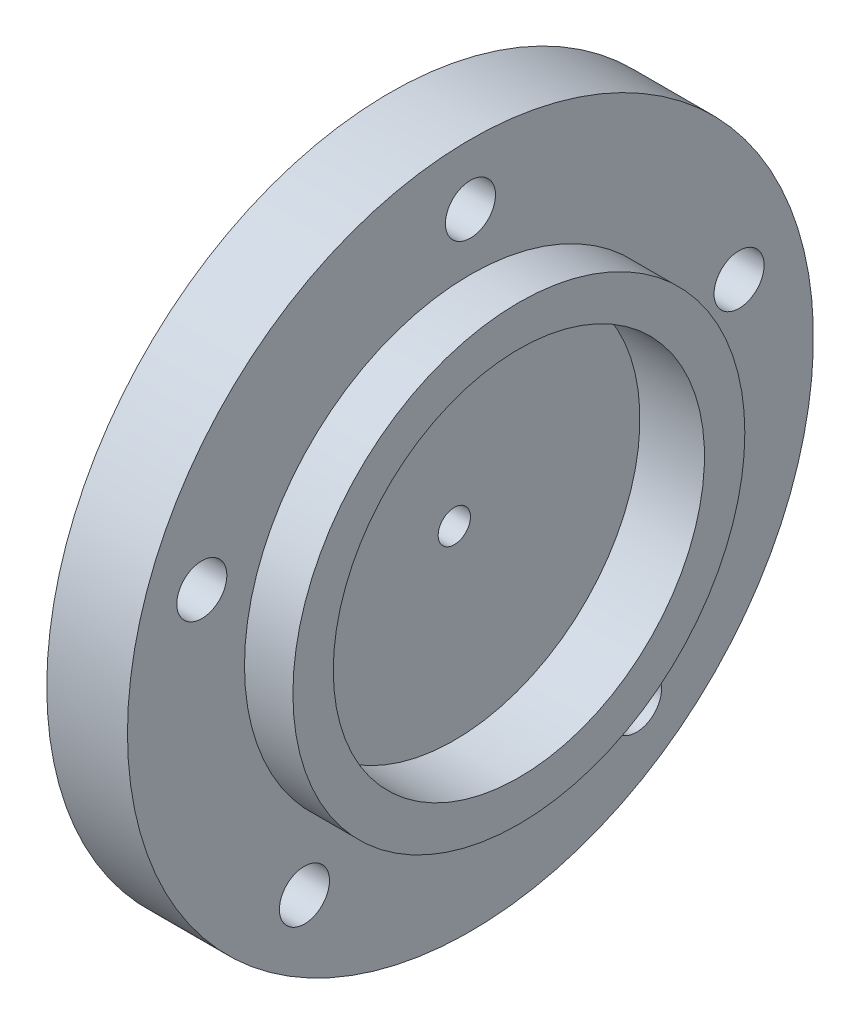
SolidWorks part; units mm, degrees
ref_plane "Спереди" through (0, 0, 0) normal (0, 0, 1) x (1, 0, 0)
ref_plane "Сверху" through (0, 0, 0) normal (0, 1, 0) x (1, 0, 0)
ref_plane "Справа" through (0, 0, 0) normal (1, 0, 0) x (0, 0, -1)
sketch "Эскиз1" plane through (0, 0, 0) normal (0, 0, 1) x (1, 0, 0)
  line L0 (-696.0458, 0) -> (34106.2443, 0) construction
  line L1 (0, -696.0458) -> (0, 34106.2443) construction
  line L2 (0, -2) -> (8, -2)
  line L3 (8, -2) -> (8, -23)
  line L4 (8, -23) -> (16, -23)
  line L5 (16, -23) -> (16, -28)
  line L6 (16, -28) -> (10, -28)
  line L7 (10, -28) -> (10, -42.5)
  line L8 (10, -42.5) -> (0, -42.5)
  line L9 (0, -42.5) -> (0, -2)
  dimension "D1" = 85
  dimension "D2" = 56
  dimension "D3" = 46
  dimension "D4" = 4
  dimension "D5" = 8
  dimension "D6" = 10
  dimension "D7" = 16
revolve "Повернуть1" add sketch "Эскиз1" angle 360 about L0
sketch "Эскиз2" plane through (0, 0, 0) normal (-1, 0, 0) x (0, 0, 1)
  line L0 (0, -1000) -> (0, 49000) construction
  circle A0 centre (0, 0) radius 35
  point P2 (0, 35)
  point P6 (33.287, 10.8156)
  point P9 (20.5725, -28.3156)
  point P10 (-20.5725, -28.3156)
  point P11 (-33.287, 10.8156)
  point P12 (0, 0)
  dimension "D1" = 70
  dimension "D2" = 5
hole_wizard "Диаметр отверстия Ø6.0 (6)1" positions "Трехмерный эскиз1" profile "Эскиз3" hole size "Ø6.0" standard "Ansi Metric" end condition up to next
sketch3d "Трехмерный эскиз1"
  point P0 (0, 10.8156, -33.287)
  point P3 (0, 10.8156, 33.287)
  point P6 (0, 35, 0)
  point P9 (0, -28.3156, -20.5725)
  point P12 (0, -28.3156, 20.5725)
sketch "Эскиз3" plane through (0, 10.8156, -33.287) normal (0, 1, 0) x (0, 0, 1)
  line L0 (0, 0) -> (0, 10)
  line L1 (0, 10) -> (3.1, 10)
  line L2 (3.1, 10) -> (3.1, 0)
  line L5 (3.1, 0) -> (0, 0)
  line L11 (0, -6.35) -> (0, 107.95) construction
  dimension "Диаметр сквозного отверстия" = 6.2
  dimension "Глубина сквозного отверстия" = 10
